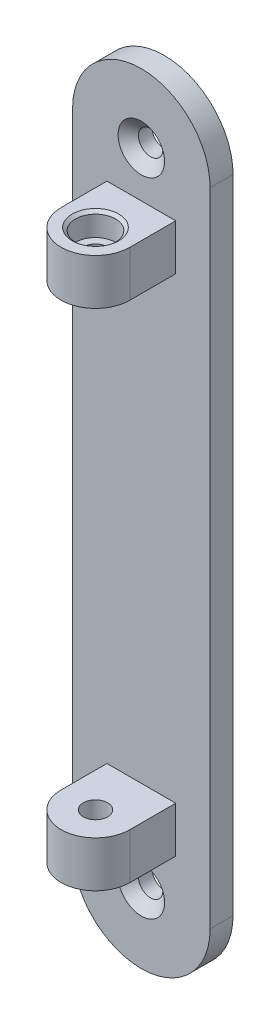
SolidWorks part; units mm, degrees
material "Plain Carbon Steel"
ref_plane "Front Plane" through (0, 0, 0) normal (0, 0, 1) x (1, 0, 0)
ref_plane "Top Plane" through (0, 0, 0) normal (0, 1, 0) x (1, 0, 0)
ref_plane "Right Plane" through (0, 0, 0) normal (1, 0, 0) x (0, 0, -1)
sketch "Sketch1" plane through (0, 0, 0) normal (0, 0, 1) x (1, 0, 0)
  line L0 (0, 0) -> (38.1, 0)
  line L1 (38.1, 0) -> (38.1, 88.9)
  line L2 (0, 88.9) -> (0, 0)
  arc A0 (38.1, 88.9) -> (0, 88.9) centre (19.05, 88.9) ccw
  dimension "D1" = 88.9
  dimension "D2" = 19.05
extrude "Boss-Extrude1" add sketch "Sketch1" along normal blind 6.35
hole_wizard "CSK for 1/4 Flat Head Machine Screw (100)1" positions "Sketch2" profile "Sketch3" countersink size "1/4" standard "ANSI Inch" end condition through all
sketch "Sketch2" plane through (0, 0, 6.35) normal (0, 0, 1) x (1, 0, 0)
  arc A0 (38.1, 88.9) -> (0, 88.9) centre (19.05, 88.9) ccw construction
  point P0 (19.05, 88.9)
sketch "Sketch3" plane through (19.05, 88.9, 6.35) normal (1, 0, 0) x (0, -1, 0)
  line L0 (0, 0) -> (0, 6.35)
  line L1 (0, 6.35) -> (3.3782, 6.35)
  line L2 (3.3782, 6.35) -> (3.3782, 2.5682)
  line L3 (3.3782, 2.5682) -> (6.4389, 0)
  line L5 (6.4389, 0) -> (0, 0)
  line L6 (-3.3782, 2.5682) -> (-6.4389, 0) construction
  line L11 (0, -6.35) -> (0, 107.95) construction
  dimension "Thru Hole Dia." = 6.7564
  dimension "Thru Hole Depth" = 6.35
  dimension "Near C'Sink Dia." = 12.8778
  dimension "Near C'Sink Angle" = 100
sketch "Sketch4" plane through (0, 0, 6.35) normal (0, 0, 1) x (1, 0, 0)
  line L0 (19.05, 0) -> (19.05, 63.5) construction
  line L1 (9.525, 76.2) -> (28.575, 76.2)
  line L2 (9.525, 76.2) -> (9.525, 63.5)
  line L3 (9.525, 63.5) -> (28.575, 63.5)
  line L4 (28.575, 76.2) -> (28.575, 63.5)
  line L5 (0, 0) -> (38.1, 0) construction
  dimension "D1" = 12.7
  dimension "D2" = 19.05
  dimension "D3" = 63.5
extrude "Boss-Extrude2" add sketch "Sketch4" along normal blind 12.7 contours L2 L1 L4 L3
sketch "Sketch12" plane through (0, 76.2, 0) normal (0, 1, 0) x (1, 0, 0)
  line L0 (9.525, -19.05) -> (28.575, -19.05)
  arc A0 (28.575, -19.05) -> (9.525, -19.05) centre (19.05, -19.05) cw
extrude "Boss-Extrude4" add sketch "Sketch12" against normal up to surface (12.7 mm away) contours A0 L0 up to face at (19.05, 63.5, 12.7)
hole_wizard "CBORE for 1/4 Socket Head Cap Screw1" positions "Sketch13" profile "Sketch14" counterbore size "1/4" standard "ANSI Inch"
sketch "Sketch13" plane through (0, 76.2, 0) normal (0, 1, 0) x (1, 0, 0)
  arc A0 (9.525, -19.05) -> (28.575, -19.05) centre (19.05, -19.05) ccw construction
  point P0 (19.05, -19.05)
sketch "Sketch14" plane through (19.05, 76.2, 19.05) normal (1, 0, 0) x (0, 0, 1)
  line L0 (0, 0) -> (0, 141.7288)
  line L1 (0, 141.7288) -> (3.3782, 139.699)
  line L2 (3.3782, 139.699) -> (3.3782, 6.35)
  line L3 (3.3782, 6.35) -> (5.5562, 6.35)
  line L5 (5.5562, 6.35) -> (5.5562, 0.7406)
  line L6 (5.5562, 0.7406) -> (6.4389, 0)
  line L7 (6.4389, 0) -> (0, 0)
  line L8 (-5.5562, 0.7406) -> (-6.4389, 0) construction
  line L10 (0, 141.7288) -> (-3.3782, 139.699) construction
  line L11 (0, -6.35) -> (0, 107.95) construction
  dimension "Hole Dia." = 6.7564
  dimension "Hole Depth" = 139.699
  dimension "C'Bore Dia." = 11.1125
  dimension "C'Bore Depth" = 6.35
  dimension "Near C'Sink Dia." = 12.8778
  dimension "Near C'Sink Angle" = 100
  dimension "Drill Angle" = 118
mirror "Mirror3" about plane through (0, 0, 6.35) normal (0, 1, 0) of "Boss-Extrude1", "CBORE for 1/4 Socket Head Cap Screw1", "Boss-Extrude4", "Boss-Extrude2", "CSK for 1/4 Flat Head Machine Screw (100)1"
